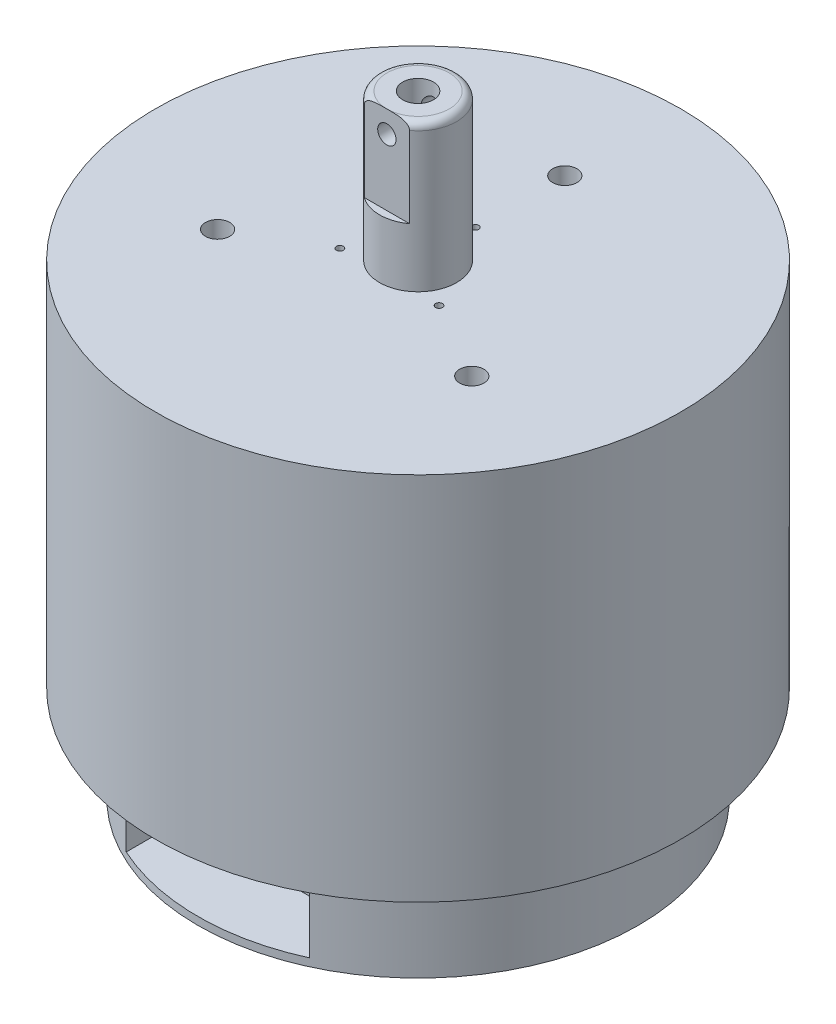
SolidWorks part; units mm, degrees
material "可锻铸铁"
ref_plane "前视基准面" through (0, 0, 0) normal (0, 0, 1) x (1, 0, 0)
ref_plane "上视基准面" through (0, 0, 0) normal (0, 1, 0) x (1, 0, 0)
ref_plane "右视基准面" through (0, 0, 0) normal (1, 0, 0) x (0, 0, -1)
sketch "草图1" plane through (0, 0, 0) normal (1, 0, 0) x (0, 0, -1)
  line L0 (0, 0) -> (0, 63.5) construction
  line L1 (0, 0) -> (-30, 0)
  line L2 (-30, 0) -> (-30, 13.0616)
  line L3 (-30, 13.0616) -> (-35.8, 13.0616)
  line L4 (-35.8, 13.0616) -> (-35.8, 63.5)
  line L5 (-35.8, 63.5) -> (0, 63.5)
  line L6 (0, 83.5) -> (0, 114.4651) construction
  line L8 (0, 63.5) -> (0, 0)
  dimension "D2" = 35.8
  dimension "D3" = 30
revolve "旋转1" add sketch "草图1" angle 360 about L0
sketch "草图2" plane through (0, 63.5, 0) normal (0, 1, 0) x (1, 0, 0)
  circle A0 centre (0, 0) radius 5.25
  dimension "D1" = 10.5
extrude "凸台-拉伸1" add sketch "草图2" along normal blind 20
hole_wizard "M4 螺纹孔1" positions "草图4" profile "草图3" tap size "M4" standard "GB"
sketch "草图4" plane through (0, 63.5, 0) normal (0, 1, 0) x (1, 0, 0)
  circle A0 centre (0, 0) radius 20 construction
  point P0 (0, 20)
  dimension "D1" = 40
sketch "草图3" plane through (0, 63.5, -20) normal (1, 0, 0) x (0, 0, 1)
  line L0 (0, 0) -> (0, 4.9914)
  line L1 (0, 4.9914) -> (1.65, 4)
  line L2 (1.65, 4) -> (1.65, 0)
  line L5 (1.65, 0) -> (0, 0)
  line L10 (0, 4.9914) -> (-1.65, 4) construction
  line L11 (0, -6.35) -> (0, 107.95) construction
  dimension "螺纹孔钻头直径" = 3.3
  dimension "螺纹孔钻头深度" = 4
  dimension "导头角度" = 118
cosmetic thread "孔螺蚊线1" parameters "D1"=4, "D2"=4
hole_wizard "M1.2x0.25 螺纹孔1" positions "草图6" profile "草图5" tap size "M1.2x0.25" standard "GB"
sketch "草图6" plane through (0, 63.5, 0) normal (0, 1, 0) x (1, 0, 0)
  circle A0 centre (0, 0) radius 7.8
  point P0 (0, 7.8)
sketch "草图5" plane through (0, 63.5, -7.8) normal (1, 0, 0) x (0, 0, 1)
  line L0 (0, 0) -> (0, 3.4354)
  line L1 (0, 3.4354) -> (0.475, 3.15)
  line L2 (0.475, 3.15) -> (0.475, 0)
  line L5 (0.475, 0) -> (0, 0)
  line L10 (0, 3.4354) -> (-0.475, 3.15) construction
  line L11 (0, -6.35) -> (0, 107.95) construction
  dimension "螺纹孔钻头直径" = 0.95
  dimension "螺纹孔钻头深度" = 3.15
  dimension "导头角度" = 118
cosmetic thread "孔螺蚊线2" parameters "D1"=2.4, "D2"=1.2
pattern_circular "阵列(圆周)1" count 3 over 360 about axis through (0, 0, 0) along (0, 1, 0) of "M4 螺纹孔1", "M1.2x0.25 螺纹孔1"
sketch3d "3D草图1" plane through (0, 0, 0) normal (0, 0, 1) x (1, 0, 0)
  dimension "D1" = 40
sketch "草图7" plane through (0, 0, 40) normal (0, 0, 1) x (1, 0, 0)
  line L0 (-30, 13.0616) -> (30, 13.0616) construction
  line L1 (-12.5, 13.0616) -> (12.5, 13.0616)
  line L2 (-12.5, 13.0616) -> (-12.5, 1.0616)
  line L3 (-12.5, 1.0616) -> (12.5, 1.0616)
  line L4 (12.5, 13.0616) -> (12.5, 1.0616)
  line L5 (-12.5, 13.0616) -> (12.5, 1.0616) construction
  line L6 (-12.5, 1.0616) -> (12.5, 13.0616) construction
  line L7 (-30, 13.0616) -> (30, 13.0616) construction
  point P0 (0, 7.0616)
  dimension "D1" = 25
  dimension "D2" = 12
extrude "切除-拉伸1" cut sketch "草图7" against normal blind 20
fillet "圆角1" radius 1 1 edges at (0, 83.5, 5.25)
sketch3d "3D草图2" plane through (0, 0, 0) normal (0, 0, 1) x (1, 0, 0)
  dimension "D1" = 4.25
sketch "草图9" plane through (0, 0, 4.25) normal (0, 0, 1) x (1, 0, 0)
  line L0 (5.25, 83.5) -> (-5.25, 83.5) construction
  line L1 (-3.8048, 83.5) -> (3.8048, 83.5)
  line L2 (-3.8048, 83.5) -> (-3.8048, 71.5)
  line L3 (-3.8048, 71.5) -> (3.8048, 71.5)
  line L4 (3.8048, 83.5) -> (3.8048, 71.5)
  line L5 (-3.8048, 83.5) -> (3.8048, 71.5) construction
  line L6 (-3.8048, 71.5) -> (3.8048, 83.5) construction
  line L7 (0, 0) -> (0, 94.9311) construction
  point P0 (0, 77.5)
  dimension "D1" = 12
extrude "切除-拉伸2" cut sketch "草图9" along normal blind 20
hole_wizard "M3 螺纹孔1" positions "草图11" profile "草图10" tap size "M3" standard "GB" end condition through all
sketch "草图11" plane through (0, 0, 4.25) normal (0, 0, 1) x (1, 0, 0)
  line L0 (-3.0822, 71.5) -> (3.0822, 71.5) construction
  point P0 (0, 80.5)
  dimension "D1" = 9
cosmetic thread "孔螺蚊线3" parameters "D2"=3
sketch "草图10" plane through (0, 80.5, 4.25) normal (1, 0, 0) x (0, -1, 0)
  line L0 (0, 0) -> (0, 40.05)
  line L1 (0, 40.05) -> (1.25, 40.05)
  line L2 (1.25, 40.05) -> (1.25, 0)
  line L5 (1.25, 0) -> (0, 0)
  line L11 (0, -6.35) -> (0, 107.95) construction
  dimension "通孔螺纹孔钻头直径" = 2.5
  dimension "通孔螺纹孔钻头深度" = 40.05
hole_wizard "M5 螺纹孔1" positions "草图13" profile "草图12" tap size "M5" standard "GB"
sketch "草图13" plane through (0, 83.5, 0) normal (0, 1, 0) x (1, 0, 0)
  point P0 (0, 0)
cosmetic thread "孔螺蚊线4" parameters "D1"=6, "D2"=5
sketch "草图12" plane through (0, 83.5, 0) normal (1, 0, 0) x (0, 0, 1)
  line L0 (0, 0) -> (0, 11.2618)
  line L1 (0, 11.2618) -> (2.1, 10)
  line L2 (2.1, 10) -> (2.1, 0)
  line L5 (2.1, 0) -> (0, 0)
  line L10 (0, 11.2618) -> (-2.1, 10) construction
  line L11 (0, -6.35) -> (0, 107.95) construction
  dimension "螺纹孔钻头直径" = 4.2
  dimension "螺纹孔钻头深度" = 10
  dimension "导头角度" = 118
